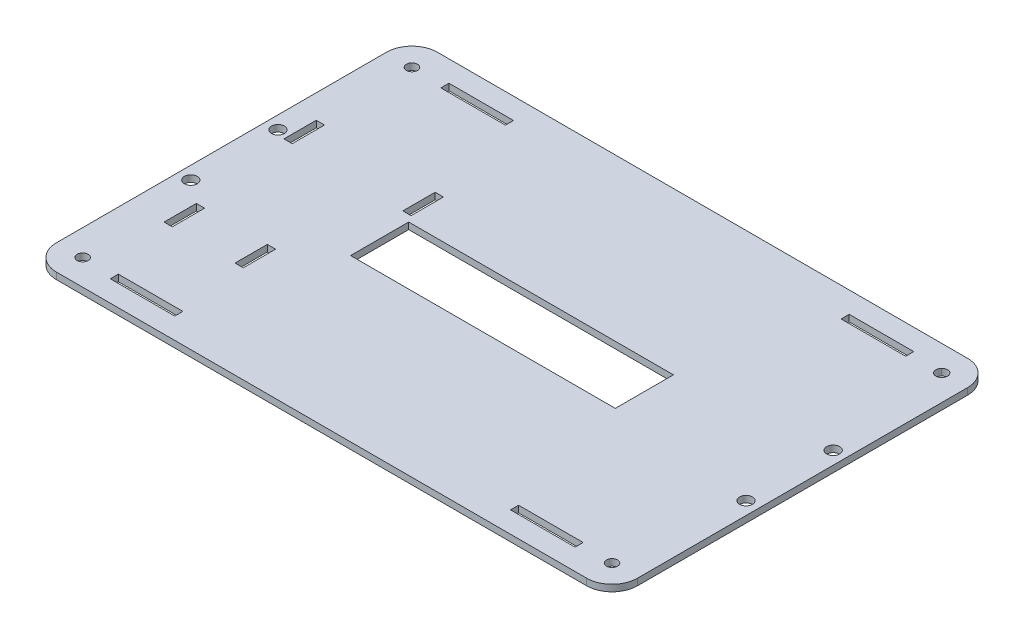
SolidWorks part; units mm, degrees
ref_plane "Front Plane" through (0, 0, 0) normal (0, 0, 1) x (1, 0, 0)
ref_plane "Top Plane" through (0, 0, 0) normal (0, 1, 0) x (1, 0, 0)
ref_plane "Right Plane" through (0, 0, 0) normal (1, 0, 0) x (0, 0, -1)
sketch "Sketch1" plane through (0, 0, 0) normal (0, 1, 0) x (1, 0, 0)
  line L0 (114.3, 0) -> (114.3, -149.86) construction
  line L1 (0, 0) -> (228.6, 0)
  line L2 (0, 0) -> (0, -149.86)
  line L3 (0, -149.86) -> (228.6, -149.86)
  line L4 (228.6, 0) -> (228.6, -149.86)
  line L5 (0, -74.93) -> (228.6, -74.93) construction
  line L6 (205.74, -11.4755) -> (180.34, -8.3005) construction
  line L7 (22.86, -8.3005) -> (48.26, -8.3005)
  line L8 (22.86, -8.3005) -> (22.86, -11.4755)
  line L9 (22.86, -11.4755) -> (48.26, -11.4755)
  line L10 (48.26, -8.3005) -> (48.26, -11.4755)
  line L11 (22.86, -8.3005) -> (48.26, -11.4755) construction
  line L12 (22.86, -11.4755) -> (48.26, -8.3005) construction
  line L13 (205.74, -8.3005) -> (180.34, -11.4755) construction
  line L14 (180.34, -8.3005) -> (180.34, -11.4755)
  line L15 (205.74, -11.4755) -> (180.34, -11.4755)
  line L16 (205.74, -8.3005) -> (205.74, -11.4755)
  line L17 (205.74, -8.3005) -> (180.34, -8.3005)
  line L18 (205.74, -141.5595) -> (180.34, -138.3845) construction
  line L19 (205.74, -138.3845) -> (180.34, -141.5595) construction
  line L20 (205.74, -141.5595) -> (180.34, -141.5595)
  line L21 (205.74, -141.5595) -> (205.74, -138.3845)
  line L22 (205.74, -138.3845) -> (180.34, -138.3845)
  line L23 (180.34, -141.5595) -> (180.34, -138.3845)
  line L24 (22.86, -138.3845) -> (48.26, -141.5595) construction
  line L25 (22.86, -141.5595) -> (48.26, -138.3845) construction
  line L26 (48.26, -141.5595) -> (48.26, -138.3845)
  line L27 (22.86, -138.3845) -> (48.26, -138.3845)
  line L28 (22.86, -141.5595) -> (22.86, -138.3845)
  line L29 (22.86, -141.5595) -> (48.26, -141.5595)
  circle A0 centre (5.08, -57.785) radius 2.54
  circle A1 centre (5.08, -92.075) radius 2.54
  circle A2 centre (223.52, -92.075) radius 2.54
  circle A3 centre (223.52, -57.785) radius 2.54
  circle A4 centre (218.44, -10.16) radius 2.159
  circle A5 centre (10.16, -10.16) radius 2.159
  circle A6 centre (218.44, -139.7) radius 2.159
  circle A7 centre (10.16, -139.7) radius 2.159
  point P25 (35.56, -9.888)
  point P34 (193.04, -9.888)
  point P39 (193.04, -139.972)
  point P44 (35.56, -139.972)
  dimension "D3" = 5.08
  dimension "D4" = 34.29
  dimension "D6" = 5.08
  dimension "D1" = 149.86
  dimension "D2" = 228.6
  dimension "D5" = 17.145
  dimension "D7" = 10.16
  dimension "D8" = 10.16
  dimension "D9" = 3.175
  dimension "D10" = 25.4
  dimension "D11" = 25.4
extrude "Boss-Extrude1" add sketch "Sketch1" along normal blind 2.6 contours L10 L7 L8 L9 | A5 | A0 | A1 | A7 | L28 L29 L26 L27 | A6 | L23 L20 L21 L22 | A2 | A3 | A4 | L16 L17 L14 L15 | L1 L4 L3 L2
fillet "Fillet1" radius 10 4 edges at (0, 1.3, 0) (0, 1.3, 149.86) (228.6, 1.3, 149.86) (228.6, 1.3, 0)
sketch "Sketch6" plane through (0, 0, 0) normal (0, -1, 0) x (1, 0, 0)
  line L0 (228.6, 10) -> (228.6, 139.86) construction
  line L1 (10, 0) -> (218.6, 0) construction
  circle A0 centre (218.6, 10) radius 2.159
  dimension "D1" = 4.318
  dimension "D2" = 10
  dimension "D3" = 10
extrude "Cut-Extrude6" cut sketch "Sketch6" against normal blind 2.6 contours A0
sketch "Sketch15" plane through (0, 0, 0) normal (0, -1, 0) x (1, 0, 0)
  line L0 (114.3, 0) -> (114.3, 149.86) construction
  line L2 (0, 74.93) -> (228.6, 74.93) construction
  line L4 (0, 10) -> (0, 139.86) construction
  line L5 (228.6, 10) -> (228.6, 139.86) construction
  line L6 (10, 0) -> (218.6, 0) construction
  line L7 (10, 149.86) -> (218.6, 149.86) construction
  circle A0 centre (114.3, 74.93) radius 10
  dimension "D1" = 20
extrude "Cut-Extrude14" cut sketch "Sketch15" against normal through all contours A0
sketch "Sketch25" plane through (0, 2.6, 0) normal (0, 1, 0) x (1, 0, 0)
  line L0 (114.3, 0) -> (114.3, -149.86) construction
  line L1 (62.23, -86.36) -> (166.37, -86.36)
  line L2 (62.23, -86.36) -> (62.23, -63.5)
  line L3 (62.23, -63.5) -> (166.37, -63.5)
  line L4 (166.37, -86.36) -> (166.37, -63.5)
  line L5 (10, 0) -> (218.6, 0) construction
  line L6 (10, -149.86) -> (218.6, -149.86) construction
  line L7 (0, -74.93) -> (228.6, -74.93) construction
  line L8 (0, -10) -> (0, -139.86) construction
  line L9 (228.6, -10) -> (228.6, -139.86) construction
  line L10 (9.3722, -53.364) -> (12.6107, -53.364) construction
  line L11 (9.3722, -47.014) -> (12.6107, -47.014)
  line L12 (9.3722, -47.014) -> (9.3722, -59.714)
  line L13 (9.3722, -59.714) -> (12.6107, -59.714)
  line L14 (12.6107, -47.014) -> (12.6107, -59.714)
  line L15 (57.2893, -48.157) -> (60.5278, -48.157)
  line L16 (57.2893, -48.157) -> (57.2893, -60.857)
  line L17 (57.2893, -60.857) -> (60.5278, -60.857)
  line L18 (60.5278, -48.157) -> (60.5278, -60.857)
  line L19 (14.122, -111.6443) -> (17.3605, -111.6443)
  line L20 (14.122, -111.6443) -> (14.122, -98.9443)
  line L21 (14.122, -98.9443) -> (17.3605, -98.9443)
  line L22 (17.3605, -111.6443) -> (17.3605, -98.9443)
  line L23 (42.0493, -111.6443) -> (45.2878, -111.6443)
  line L24 (42.0493, -111.6443) -> (42.0493, -98.9443)
  line L25 (42.0493, -98.9443) -> (45.2878, -98.9443)
  line L26 (45.2878, -111.6443) -> (45.2878, -98.9443)
  line L27 (57.2893, -54.507) -> (60.5278, -54.507) construction
  line L28 (14.122, -105.2943) -> (17.3605, -105.2943) construction
  line L29 (42.0493, -105.2943) -> (45.2878, -105.2943) construction
  point P16 (114.3, -63.5)
  point P17 (166.37, -74.93)
  dimension "D3" = 12.7
  dimension "D1" = 104.14
  dimension "D2" = 22.86
extrude "Cut-Extrude18" cut sketch "Sketch25" against normal blind 10.16
